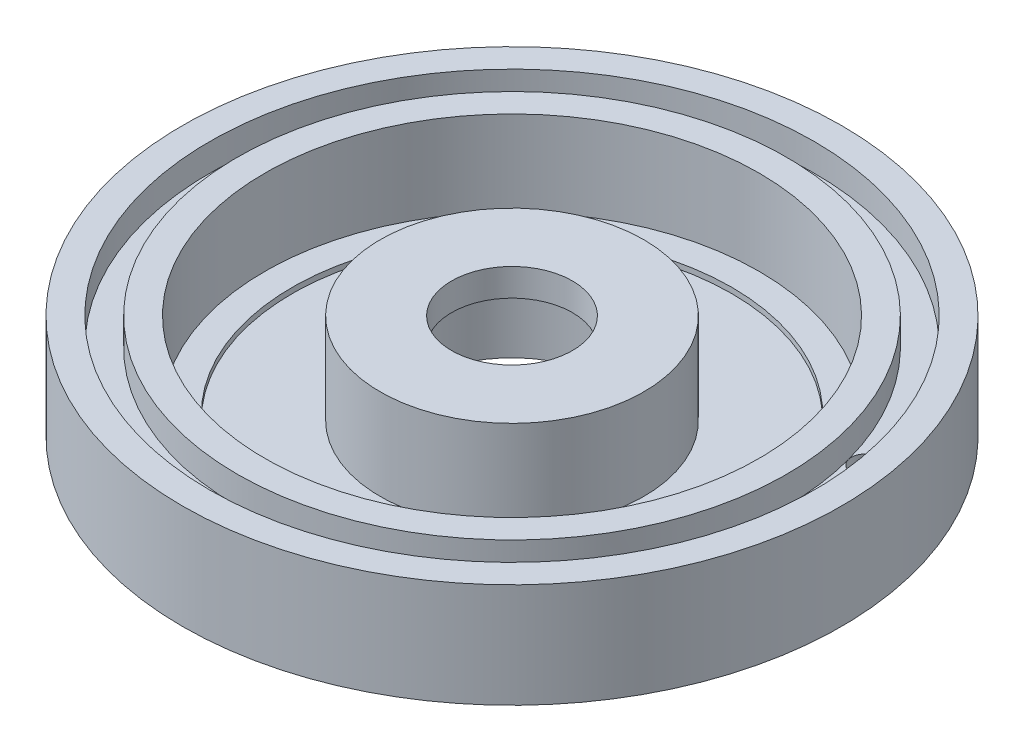
SolidWorks part; units mm, degrees
ref_plane "Front Plane" through (0, 0, 0) normal (0, 0, 1) x (1, 0, 0)
ref_plane "Top Plane" through (0, 0, 0) normal (0, 1, 0) x (1, 0, 0)
ref_plane "Right Plane" through (0, 0, 0) normal (1, 0, 0) x (0, 0, -1)
sketch "Sketch1" plane through (0, 0, 0) normal (0, 1, 0) x (1, 0, 0)
  circle A0 centre (0, 0) radius 60
  dimension "D1" = 120
extrude "Boss-Extrude1" add sketch "Sketch1" along normal blind 19
sketch "Sketch2" plane through (0, 19, 0) normal (0, 1, 0) x (1, 0, 0)
  circle A0 centre (0, 0) radius 55
  circle A1 centre (0, 0) radius 50
  circle A2 centre (0, 0) radius 60 construction
  dimension "D1" = 5
  dimension "D2" = 5
extrude "Cut-Extrude1" cut sketch "Sketch2" against normal blind 5
sketch "Sketch4" plane through (0, 0, 0) normal (0, 0, 1) x (1, 0, 0)
  line L0 (45, 19) -> (45, 3.5)
  line L1 (60, 19) -> (-60, 19) construction
  line L11 (50, 19) -> (-50, 19) construction
  line L12 (0, 19) -> (45, 19)
  line L13 (0, 0) -> (0, 44.729) construction
  line L18 (0, 19) -> (0, 2.5)
  line L19 (45, 3.5) -> (40, 3.5)
  line L20 (40, 3.5) -> (40, 2.5)
  line L21 (40, 2.5) -> (0, 2.5)
  dimension "D1" = 90
  dimension "D2" = 15.5
  dimension "D7" = 1
  dimension "D8" = 80
revolve "Cut-Revolve1" cut sketch "Sketch4" angle 360 about L13
sketch "Sketch5" plane through (0, 0, 0) normal (0, 0, 1) x (1, 0, 0)
  line L0 (17.5, 0) -> (17.5, 14)
  line L2 (17.5, 14) -> (11, 14)
  line L3 (11, 14) -> (11, 19)
  line L5 (11, 19) -> (24, 19)
  line L6 (24, 19) -> (24, 0)
  line L7 (24, 0) -> (17.5, 0)
  line L8 (0, 0) -> (0, 29.0545) construction
  line L11 (60, 19) -> (-60, 19) construction
  line L12 (-60, 0) -> (60, 0) construction
  dimension "D1" = 35
  dimension "D2" = 48
  dimension "D3" = 22
  dimension "D4" = 5
revolve "Revolve1" add sketch "Sketch5" angle 360 about L8
sketch "Sketch6" plane through (0, 0, 0) normal (0, 0, 1) x (1, 0, 0)
  line L0 (0, 14) -> (0, 37.8962) construction
  line L1 (0, 0) -> (17.5, 0)
  line L2 (0, 0) -> (0, 14)
  line L3 (0, 14) -> (17.5, 14)
  line L4 (17.5, 0) -> (17.5, 14)
  line L5 (-17.5, 14) -> (17.5, 14) construction
  dimension "D1" = 35
revolve "Cut-Revolve2" cut sketch "Sketch6" angle 360 about L2
hole_wizard "M6 Tapped Hole1" positions "Sketch7" profile "Sketch8" tap size "M6" standard "ISO"
sketch "Sketch7" plane through (0, 19, 0) normal (0, 1, 0) x (1, 0, 0)
  point P0 (50.7111, 13.588)
  point P3 (50.7111, -13.588)
sketch "Sketch8" plane through (50.7111, 19, -13.588) normal (1, 0, 0) x (0, 0, 1)
  line L0 (0, 0) -> (0, 16.5022)
  line L1 (0, 16.5022) -> (2.5, 15)
  line L2 (2.5, 15) -> (2.5, 0)
  line L5 (2.5, 0) -> (0, 0)
  line L10 (0, 16.5022) -> (-2.5, 15) construction
  line L11 (0, -6.35) -> (0, 107.95) construction
  dimension "Tap Drill Dia." = 5
  dimension "Tap Drill Depth" = 15
  dimension "Drill Angle" = 118
cosmetic thread "Hole Thread1" parameters "D1"=12, "D2"=6
cosmetic thread "Hole Thread2" parameters "D1"=12, "D2"=6
